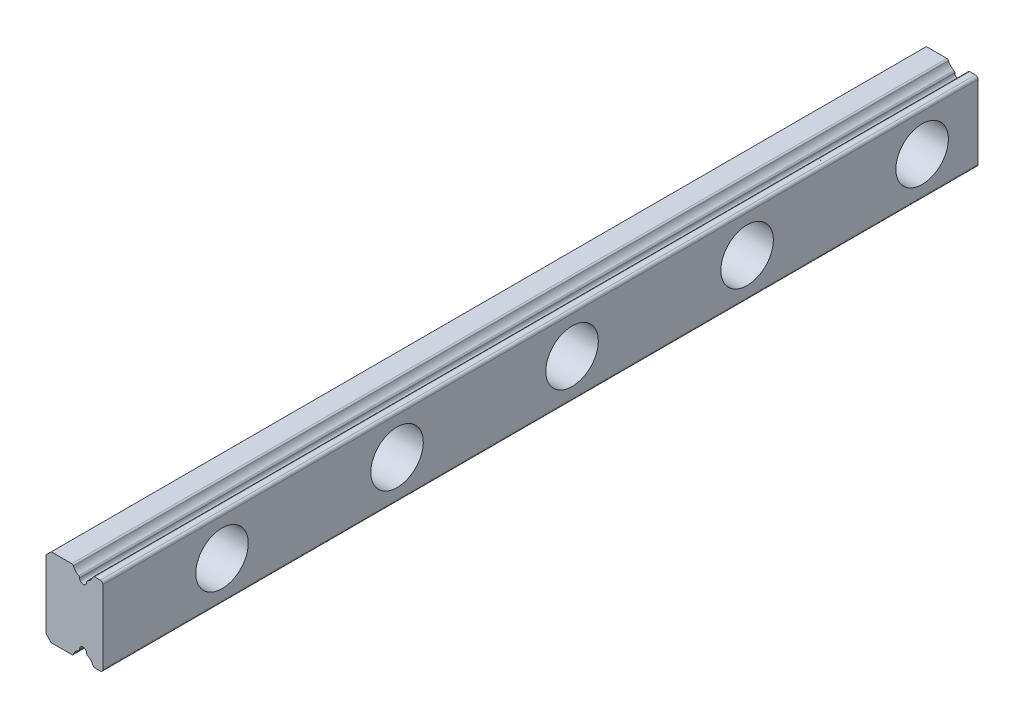
SolidWorks part; units mm, degrees
material "AISI 304"
ref_plane "前视基准面" through (0, 0, 0) normal (0, 0, 1) x (1, 0, 0)
ref_plane "上视基准面" through (0, 0, 0) normal (0, 1, 0) x (1, 0, 0)
ref_plane "右视基准面" through (0, 0, 0) normal (1, 0, 0) x (0, 0, -1)
other "Configuration Table"
sketch "草图1" plane through (0, 0, 0) normal (0, 0, 1) x (1, 0, 0)
  line L0 (2.95, 4.5) -> (2.3077, 4.5)
  line L1 (1.4, 3.5351) -> (1.4, 3.5)
  line L2 (0.6, 3.5) -> (0.6, 3.5351)
  line L3 (-0.3077, 4.5) -> (-2.65, 4.5)
  line L4 (-2.65, 4.5) -> (-3.25, 3.9)
  line L5 (-3.25, 3.9) -> (-3.25, -3.9)
  line L6 (-3.25, -3.9) -> (-2.65, -4.5)
  line L7 (-2.65, -4.5) -> (-0.3077, -4.5)
  line L8 (0.6, -3.5351) -> (0.6, -3.5)
  line L9 (1.4, -3.5) -> (1.4, -3.5351)
  line L10 (2.3077, -4.5) -> (2.95, -4.5)
  line L11 (3.25, -4.2) -> (3.25, 4.2)
  arc A0 (3.25, 4.2) -> (2.95, 4.5) centre (2.95, 4.2) ccw
  arc A1 (2.3077, 4.5) -> (2.1209, 4.3714) centre (2.3077, 4.3) ccw
  arc A2 (1.5143, 3.7158) -> (2.1209, 4.3714) centre (1, 4.8) ccw
  arc A3 (1.5143, 3.7158) -> (1.4, 3.5351) centre (1.6, 3.5351) ccw
  arc A4 (0.6, 3.5) -> (1.4, 3.5) centre (1, 3.5) ccw
  arc A5 (0.6, 3.5351) -> (0.4857, 3.7158) centre (0.4, 3.5351) ccw
  arc A6 (-0.1209, 4.3714) -> (0.4857, 3.7158) centre (1, 4.8) ccw
  arc A7 (-0.1209, 4.3714) -> (-0.3077, 4.5) centre (-0.3077, 4.3) ccw
  arc A8 (-0.3077, -4.5) -> (-0.1209, -4.3714) centre (-0.3077, -4.3) ccw
  arc A9 (0.4857, -3.7158) -> (-0.1209, -4.3714) centre (1, -4.8) ccw
  arc A10 (0.4857, -3.7158) -> (0.6, -3.5351) centre (0.4, -3.5351) ccw
  arc A11 (1.4, -3.5) -> (0.6, -3.5) centre (1, -3.5) ccw
  arc A12 (1.4, -3.5351) -> (1.5143, -3.7158) centre (1.6, -3.5351) ccw
  arc A13 (2.1209, -4.3714) -> (1.5143, -3.7158) centre (1, -4.8) ccw
  arc A14 (2.1209, -4.3714) -> (2.3077, -4.5) centre (2.3077, -4.3) ccw
  arc A15 (2.95, -4.5) -> (3.25, -4.2) centre (2.95, -4.2) ccw
  dimension "D1" = 8.4
extrude "凸台-拉伸1" add sketch "草图1" along normal blind 100
sketch "草图2" plane through (3.25, 0, 0) normal (1, 0, 0) x (0, 0, -1)
  circle A0 centre (-6.3866, 0) radius 1.75
  circle A1 centre (-26.3866, 0) radius 1.75
  circle A2 centre (-46.3866, 0) radius 1.75
  circle A3 centre (-66.3866, 0) radius 1.75
  circle A4 centre (-86.3866, 0) radius 1.75
  dimension "D1" = 3.5
  dimension "D2" = 5
extrude "切除-拉伸1" cut sketch "草图2" against normal blind 100
sketch "草图3" plane through (3.25, 0, 0) normal (1, 0, 0) x (0, 0, -1)
  circle A0 centre (-6.3866, 0) radius 3
  circle A1 centre (-26.3866, 0) radius 3
  circle A2 centre (-46.3866, 0) radius 3
  circle A3 centre (-66.3866, 0) radius 3
  circle A4 centre (-86.3866, 0) radius 3
  dimension "D1" = 6
  dimension "D2" = 5
extrude "切除-拉伸2" cut sketch "草图3" against normal blind 4.5
